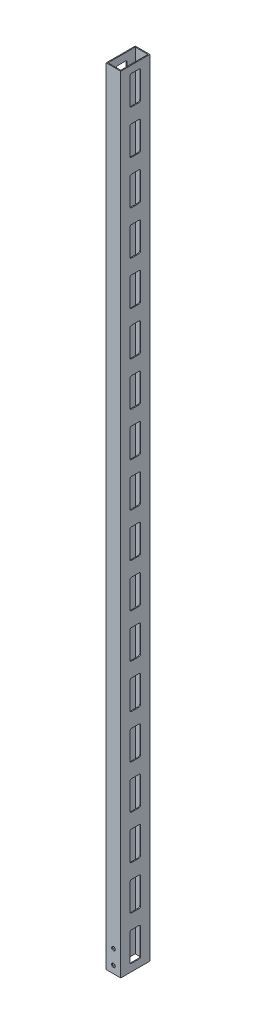
SolidWorks part; units mm, degrees
material "6061-T6 (SS)"
ref_plane "Front Plane" through (0, 0, 0) normal (0, 0, 1) x (1, 0, 0)
ref_plane "Top Plane" through (0, 0, 0) normal (0, 1, 0) x (1, 0, 0)
ref_plane "Right Plane" through (0, 0, 0) normal (1, 0, 0) x (0, 0, -1)
ref_plane "Plane1" through (0, 63.5, 0) normal (0, -1, 0) x (-1, 0, 0)
sketch "Sketch2" plane through (0, 63.5, 0) normal (0, -1, 0) x (-1, 0, 0)
  line L0 (-260.35, 190.5) -> (-260.35, 241.3) construction
  line L1 (-260.35, 241.3) -> (-234.95, 241.3) construction
  line L2 (-234.95, 190.5) -> (-234.95, 241.3) construction
  line L3 (-260.35, 190.5) -> (-234.95, 190.5) construction
  line L4 (-260.35, 190.5) -> (-260.35, 241.3)
  line L5 (-260.35, 241.3) -> (-234.95, 241.3)
  line L6 (-234.95, 190.5) -> (-234.95, 241.3)
  line L7 (-260.35, 190.5) -> (-234.95, 190.5)
  line L8 (-258.7625, 192.0875) -> (-236.5375, 192.0875)
  line L9 (-236.5375, 192.0875) -> (-236.5375, 239.7125)
  line L10 (-258.7625, 239.7125) -> (-236.5375, 239.7125)
  line L11 (-258.7625, 192.0875) -> (-258.7625, 239.7125)
  dimension "D1" = 1.5875
extrude "Boss-Extrude1" add sketch "Sketch2" against normal up to vertex (1371.6 mm away)
sketch "Sketch3" plane through (0, 0, 0) normal (0, 0, 1) x (1, 0, 0)
  circle A0 centre (247.65, 76.2) radius 3.175 construction
  circle A1 centre (247.65, 101.6) radius 3.175 construction
  circle A2 centre (247.65, 76.2) radius 3.175
  circle A3 centre (247.65, 101.6) radius 3.175
extrude "Cut-Extrude1" cut sketch "Sketch3" against normal through all
sketch "Sketch4" plane through (260.35, 0, 0) normal (1, 0, 0) x (0, 0, -1)
  line L0 (215.9, 101.6) -> (215.9, 63.5) construction
  line L1 (222.25, 127) -> (209.55, 127)
  line L2 (225.425, 123.825) -> (225.425, 79.375)
  line L3 (222.25, 76.2) -> (209.55, 76.2)
  line L4 (206.375, 123.825) -> (206.375, 79.375)
  line L5 (225.425, 127) -> (206.375, 76.2) construction
  line L6 (225.425, 76.2) -> (206.375, 127) construction
  line L7 (241.3, 63.5) -> (190.5, 63.5) construction
  arc A0 (225.425, 79.375) -> (222.25, 76.2) centre (222.25, 79.375) cw
  arc A1 (222.25, 127) -> (225.425, 123.825) centre (222.25, 123.825) cw
  arc A2 (209.55, 76.2) -> (206.375, 79.375) centre (209.55, 79.375) cw
  arc A3 (209.55, 127) -> (206.375, 123.825) centre (209.55, 123.825) ccw
  point P0 (215.9, 101.6)
  dimension "D4" = 3.175
  dimension "D1" = 19.05
  dimension "D2" = 50.8
  dimension "D3" = 38.1
extrude "Cut-Extrude2" cut sketch "Sketch4" against normal through all
pattern_linear "LPattern1" count 18 spacing 76.2 along (0, 1, 0) of "Cut-Extrude2"
